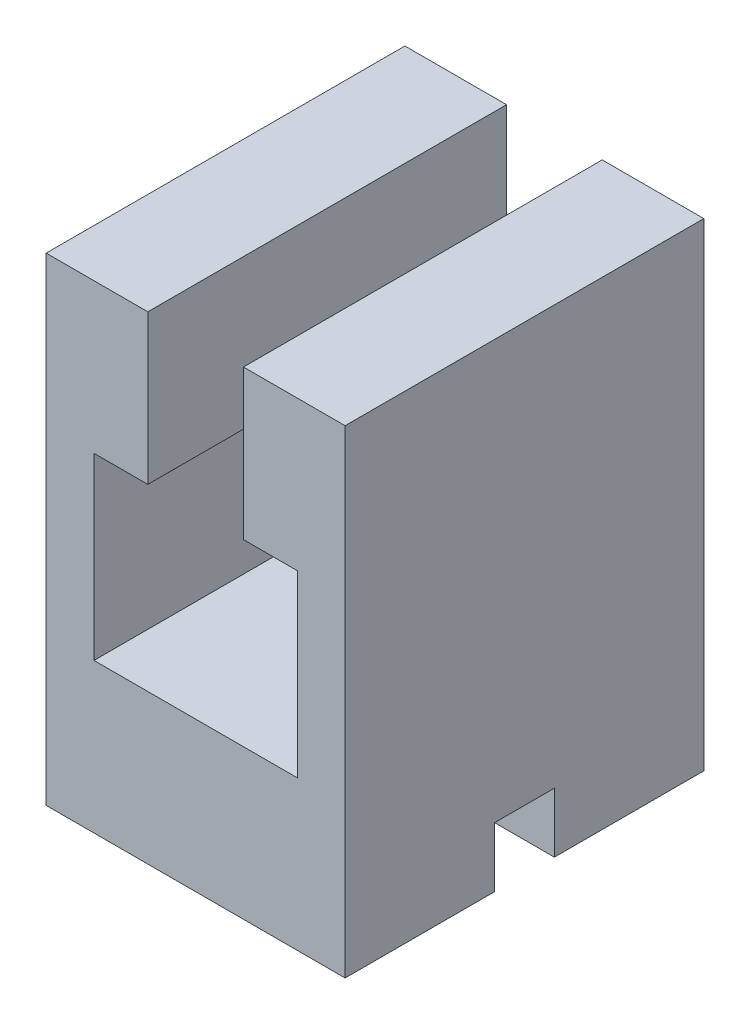
SolidWorks part; units mm, degrees
ref_plane "Front Plane" through (0, 0, 0) normal (0, 0, 1) x (1, 0, 0)
ref_plane "Top Plane" through (0, 0, 0) normal (0, 1, 0) x (1, 0, 0)
ref_plane "Right Plane" through (0, 0, 0) normal (1, 0, 0) x (0, 0, -1)
sketch "Sketch1" plane through (0, 0, 0) normal (0, 0, 1) x (1, 0, 0)
  line L0 (-50.5404, -30.6751) -> (-0.5404, -30.6751)
  line L1 (-0.5404, -30.6751) -> (-0.5404, 49.3249)
  line L2 (-0.5404, 49.3249) -> (-17.5404, 49.3249)
  line L3 (-17.5404, 49.3249) -> (-17.5404, 24.3249)
  line L4 (-17.5404, 24.3249) -> (-8.5404, 24.3249)
  line L5 (-8.5404, 24.3249) -> (-8.5404, -5.6751)
  line L6 (-8.5404, -5.6751) -> (-42.5404, -5.6751)
  line L7 (-42.5404, -5.6751) -> (-42.5404, 24.3249)
  line L8 (-42.5404, 24.3249) -> (-33.5404, 24.3249)
  line L9 (-33.5404, 24.3249) -> (-33.5404, 49.3249)
  line L10 (-33.5404, 49.3249) -> (-50.5404, 49.3249)
  line L11 (-50.5404, 49.3249) -> (-50.5404, -30.6751)
extrude "Boss-Extrude2" add sketch "Sketch1" along normal blind 60
sketch "Sketch2" plane through (-50.5404, 0, 0) normal (-1, 0, 0) x (0, 0, 1)
  line L0 (60, -30.6751) -> (0, -30.6751) construction
  line L1 (0, 49.3249) -> (0, -30.6751) construction
  line L2 (25, -30.6751) -> (35, -30.6751)
  line L3 (25, -30.6751) -> (25, -20.6751)
  line L4 (25, -20.6751) -> (35, -20.6751)
  line L5 (35, -30.6751) -> (35, -20.6751)
  line L6 (60, 49.3249) -> (60, -30.6751) construction
  dimension "D1" = 25
  dimension "D2" = 25
extrude "Cut-Extrude1" cut sketch "Sketch2" against normal blind 60
